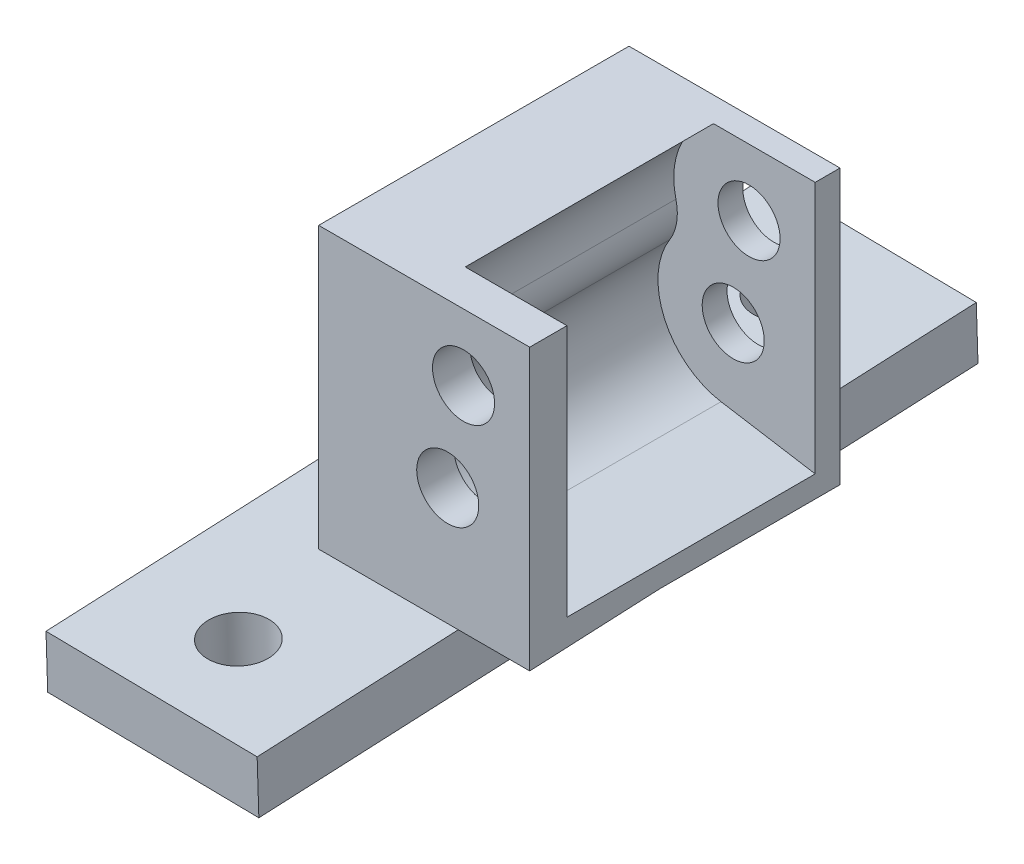
SolidWorks part; units mm, degrees
ref_plane "Front Plane" through (0, 0, 0) normal (0, 0, 1) x (1, 0, 0)
ref_plane "Top Plane" through (0, 0, 0) normal (0, 1, 0) x (1, 0, 0)
ref_plane "Right Plane" through (0, 0, 0) normal (1, 0, 0) x (0, 0, -1)
sketch "Sketch1" plane through (0, 0, 0) normal (0, 0, 1) x (1, 0, 0)
  line L0 (-449.2279, 278.7761) -> (-470.8179, 278.7761)
  line L1 (-470.8179, 278.7761) -> (-470.8179, 250.7114)
  line L2 (-470.8179, 250.7114) -> (-449.2279, 250.7114)
  line L3 (-449.2279, 250.7114) -> (-449.2279, 278.7761)
  line L4 (-427.4923, 249.3739) -> (-458.8626, 254.5214) construction
  line L5 (-427.4923, 249.3739) -> (-458.8626, 254.5214)
  line L6 (-449.2279, 252.9405) -> (-458.8626, 254.5214)
  arc A0 (-463.2968, 256.9221) -> (-458.8626, 254.5214) centre (-457.6159, 262.1197) ccw construction
  arc A1 (-463.2968, 256.9221) -> (-458.8626, 254.5214) centre (-457.6159, 262.1197) ccw
  arc A2 (-454.7498, 279.5862) -> (-461.3669, 277.5061) centre (-455.9966, 271.9877) ccw construction
  arc A3 (-461.3669, 277.5061) -> (-463.4772, 270.1621) centre (-455.9966, 271.9877) ccw construction
  arc A4 (-464.1208, 266.2396) -> (-463.4772, 270.1621) centre (-468.4124, 268.9577) ccw construction
  arc A5 (-464.1208, 266.2396) -> (-464.4679, 258.6072) centre (-457.6159, 262.1197) ccw construction
  arc A6 (-464.4679, 258.6072) -> (-458.8626, 254.5214) centre (-457.6159, 262.1197) ccw construction
  arc A7 (-454.7498, 279.5862) -> (-461.3669, 277.5061) centre (-455.9966, 271.9877) ccw
  arc A8 (-461.3669, 277.5061) -> (-463.4772, 270.1621) centre (-455.9966, 271.9877) ccw
  arc A9 (-464.1208, 266.2396) -> (-463.4772, 270.1621) centre (-468.4124, 268.9577) ccw
  arc A10 (-464.1208, 266.2396) -> (-464.4679, 258.6072) centre (-457.6159, 262.1197) ccw
  arc A11 (-464.4679, 258.6072) -> (-458.8626, 254.5214) centre (-457.6159, 262.1197) ccw
  arc A12 (-458.8626, 254.5214) -> (-463.2968, 256.9221) centre (-457.6159, 262.1197) cw
  arc A13 (-463.2968, 256.9221) -> (-464.4679, 258.6072) centre (-457.6159, 262.1197) cw
  arc A14 (-464.4679, 258.6072) -> (-464.1208, 266.2396) centre (-457.6159, 262.1197) cw
  arc A15 (-464.1208, 266.2396) -> (-463.4772, 270.1621) centre (-468.4124, 268.9577) ccw
  arc A16 (-463.4772, 270.1621) -> (-461.3669, 277.5061) centre (-455.9966, 271.9877) cw
  arc A17 (-461.3669, 277.5061) -> (-459.6312, 278.7761) centre (-455.9966, 271.9877) cw
  dimension "D1" = 3.81
  dimension "D2" = 6.35
  dimension "D3" = 21.59
  dimension "D4" = 1.27
extrude "Boss-Extrude1" add sketch "Sketch1" against normal blind 27.94 contours A11 A10 A9 A8 A7 L0 L1 L2 L3 L5 A1
sketch "Sketch2" plane through (0, 0, 0) normal (0, 0, 1) x (1, 0, 0)
  line L0 (-449.2279, 250.7114) -> (-449.2279, 252.9405) construction
  line L1 (-470.8179, 278.7761) -> (-449.2279, 278.7761)
  line L2 (-470.8179, 278.7761) -> (-470.8179, 250.7114)
  line L3 (-470.8179, 250.7114) -> (-449.2279, 250.7114)
  line L4 (-449.2279, 278.7761) -> (-449.2279, 250.7114)
  line L5 (-470.8179, 250.7114) -> (-449.2279, 250.7114) construction
  circle A0 centre (-455.9966, 271.9877) radius 3.175
  circle A1 centre (-457.6159, 262.1197) radius 3.175
  dimension "D1" = 6.35
  dimension "D2" = 6.35
extrude "Boss-Extrude2" add sketch "Sketch2" along normal blind 3.81
sketch "Sketch3" plane through (0, 0, -25.4) normal (0, 0, -1) x (-1, 0, 0)
  line L0 (449.2279, 252.9405) -> (449.2279, 278.7761)
  line L1 (449.2279, 278.7761) -> (459.6312, 278.7761)
  line L2 (458.8626, 254.5214) -> (449.2279, 252.9405)
  arc A0 (459.6312, 278.7761) -> (463.4772, 270.1621) centre (455.9966, 271.9877) cw
  arc A1 (463.4772, 270.1621) -> (464.1208, 266.2396) centre (468.4124, 268.9577) ccw
  arc A2 (464.1208, 266.2396) -> (458.8626, 254.5214) centre (457.6159, 262.1197) cw
  circle A3 centre (455.9966, 271.9877) radius 3.175
  circle A4 centre (457.6159, 262.1197) radius 3.175
  dimension "D1" = 6.35
  dimension "D2" = 6.35
extrude "Boss-Extrude3" add sketch "Sketch3" along normal up to surface (2.54 mm away) up to face at (-461.3008, 262.7522, -27.94)
ref_plane "Plane1" through (3.8456, 242.0631, 11.4172) normal (0.0159, 0.9988, 0.0471) x (0.9999, -0.0158, -0.0007)
sketch "Sketch4" plane through (3.8456, 242.0631, 11.4172) normal (0.0159, 0.9988, 0.0471) x (0.9999, -0.0158, -0.0007)
  line L0 (-482.355, 61.3462) -> (-482.355, -12.3138)
  line L1 (-482.355, -12.3138) -> (-460.765, -12.3138)
  line L2 (-460.765, -12.3138) -> (-460.765, 61.3462)
  line L3 (-460.765, 61.3462) -> (-482.355, 61.3462)
  circle A0 centre (-471.56, 52.4562) radius 3.175
  circle A1 centre (-471.56, -3.4238) radius 3.175
  dimension "D5" = 6.35
  dimension "D6" = 6.35
  dimension "D1" = 73.66
  dimension "D2" = 21.59
  dimension "D3" = 20.32
  dimension "D4" = 7.62
  dimension "D7" = 8.89
  dimension "D8" = 10.795
  dimension "D9" = 10.795
  dimension "D10" = 8.89
extrude "Boss-Extrude4" add sketch "Sketch4" against normal blind 5.588
sketch "Sketch5" plane through (-470.8179, 0, 0) normal (-1, 0, 0) x (0, 0, 1)
  line L0 (3.81, 250.7114) -> (3.81, 250.0839)
  line L1 (-49.5003, 252.5984) -> (24.0779, 249.1279) construction
  line L2 (3.81, 250.0839) -> (-13.6687, 250.9083)
  line L3 (-13.6687, 250.9083) -> (3.81, 250.7114)
extrude "Boss-Extrude5" add sketch "Sketch5" against normal up to surface (21.59 mm away) up to face at (-449.2279, 265.301, -12.3825)
